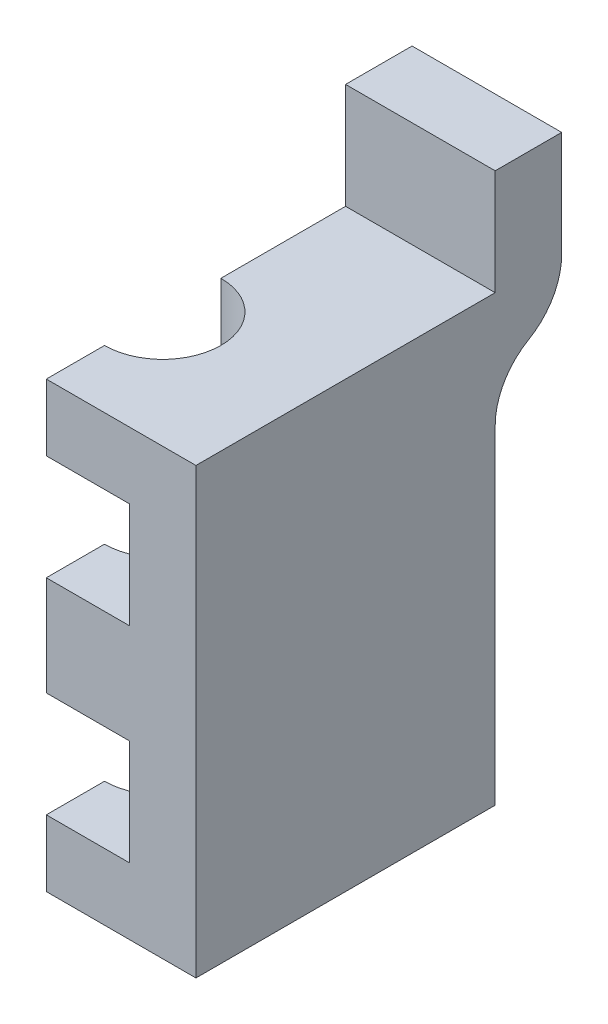
SolidWorks part; units mm, degrees
material "ABS"
ref_plane "Front Plane" through (0, 0, 0) normal (0, 0, 1) x (1, 0, 0)
ref_plane "Top Plane" through (0, 0, 0) normal (0, 1, 0) x (1, 0, 0)
ref_plane "Right Plane" through (0, 0, 0) normal (1, 0, 0) x (0, 0, -1)
sketch "Sketch5" plane through (0, 0, 0) normal (0, 0, 1) x (1, 0, 0)
  line L0 (0, 0) -> (4.5, 0)
  line L1 (0, 0) -> (0, -2)
  line L2 (0, -2) -> (2.5, -2)
  line L3 (2.5, -2) -> (2.5, -5.175)
  line L4 (2.5, -5.175) -> (0, -5.175)
  line L5 (0, -5.175) -> (0, -8.175)
  line L6 (0, -8.175) -> (2.5, -8.175)
  line L7 (2.5, -8.175) -> (2.5, -11.35)
  line L8 (2.5, -11.35) -> (0, -11.35)
  line L9 (0, -11.35) -> (0, -13.35)
  line L10 (0, -13.35) -> (4.5, -13.35)
  line L11 (4.5, -13.35) -> (4.5, 0)
  dimension "D1" = 3.175
  dimension "D2" = 2
  dimension "D3" = 3
  dimension "D4" = 2.5
  dimension "D5" = 2
extrude "Boss-Extrude3" add sketch "Sketch5" along normal mid plane 7
sketch "Sketch6" plane through (0, 0, -3.5) normal (0, 0, -1) x (-1, 0, 0)
  line L1 (-4.5, 0) -> (0, 0)
  line L2 (-4.5, 0) -> (-4.5, -13.35)
  line L3 (-4.5, -13.35) -> (0, -13.35)
  line L4 (0, 0) -> (0, -13.35)
extrude "Boss-Extrude4" add sketch "Sketch6" along normal blind 2
sketch "Sketch7" plane through (0, 0, 0) normal (0, 1, 0) x (1, 0, 0)
  circle A0 centre (0, 0) radius 1.75
  dimension "D1" = 3.5
extrude "Cut-Extrude2" cut sketch "Sketch7" against normal through all
sketch "Sketch9" plane through (0, 0, 0) normal (-1, 0, 0) x (0, 0, 1)
  line L0 (-5.5, -13.35) -> (-5.5, 0) construction
  line L1 (-7.5, 3.175) -> (-5.5, 3.175)
  line L2 (-7.5, 3.175) -> (-7.5, 0)
  line L3 (-7.5, 0) -> (-5.5, 0) construction
  line L4 (-5.5, 3.175) -> (-5.5, 0)
  line L5 (-5.5, -2) -> (-8.7413, -2) construction
  line L6 (-5.5, 0) -> (-5.5, -2)
  arc A0 (-7.5, 0) -> (-5.5, -2) centre (-5.5, 0) ccw
  dimension "D1" = 3.175
  dimension "D2" = 2
extrude "Boss-Extrude7" add sketch "Sketch9" against normal through all
fillet "Fillet1" radius 2 1 edges at (2.25, -2, -5.5)
